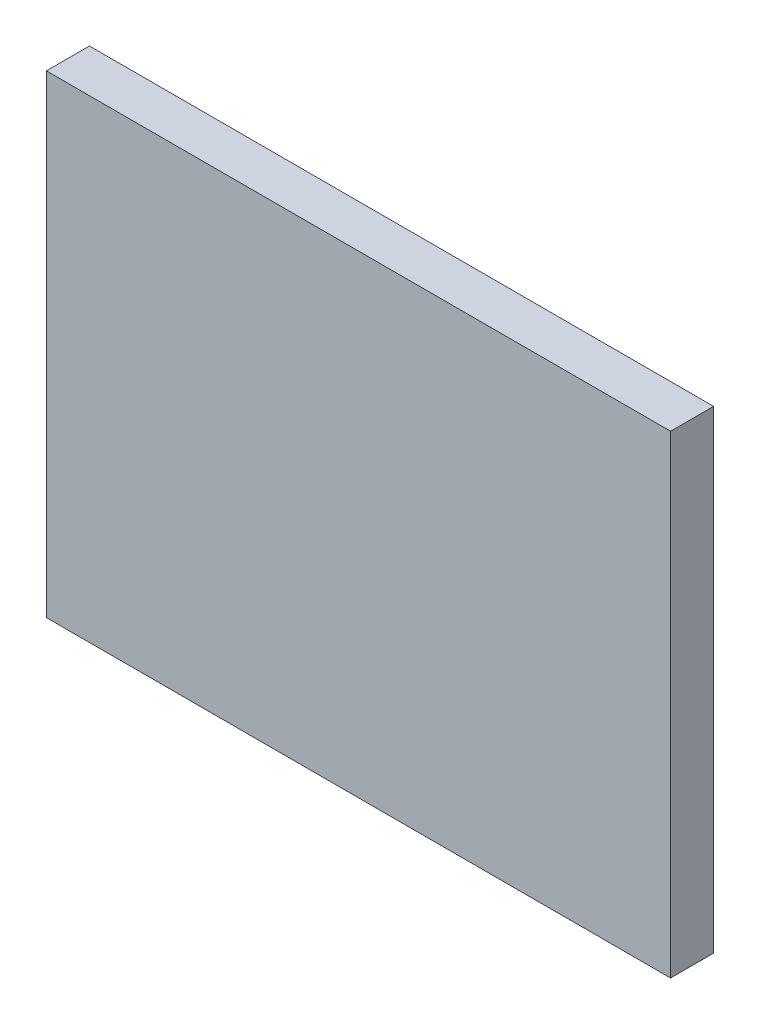
SolidWorks part; units mm, degrees
ref_plane "Front Plane" through (0, 0, 0) normal (0, 0, 1) x (1, 0, 0)
ref_plane "Top Plane" through (0, 0, 0) normal (0, 1, 0) x (1, 0, 0)
ref_plane "Right Plane" through (0, 0, 0) normal (1, 0, 0) x (0, 0, -1)
sketch "Sketch1" plane through (0, 0, 0) normal (0, 0, 1) x (1, 0, 0)
  line L1 (-72.5, 55) -> (72.5, 55)
  line L2 (-72.5, 55) -> (-72.5, -55)
  line L3 (-72.5, -55) -> (72.5, -55)
  line L4 (72.5, 55) -> (72.5, -55)
  line L5 (-72.5, 55) -> (72.5, -55) construction
  line L6 (-72.5, -55) -> (72.5, 55) construction
  point P0 (0, 0)
  dimension "D1" = 110
  dimension "D2" = 145
extrude "Boss-Extrude2" add sketch "Sketch1" along normal blind 10 contours L1 L4 L3 L2
